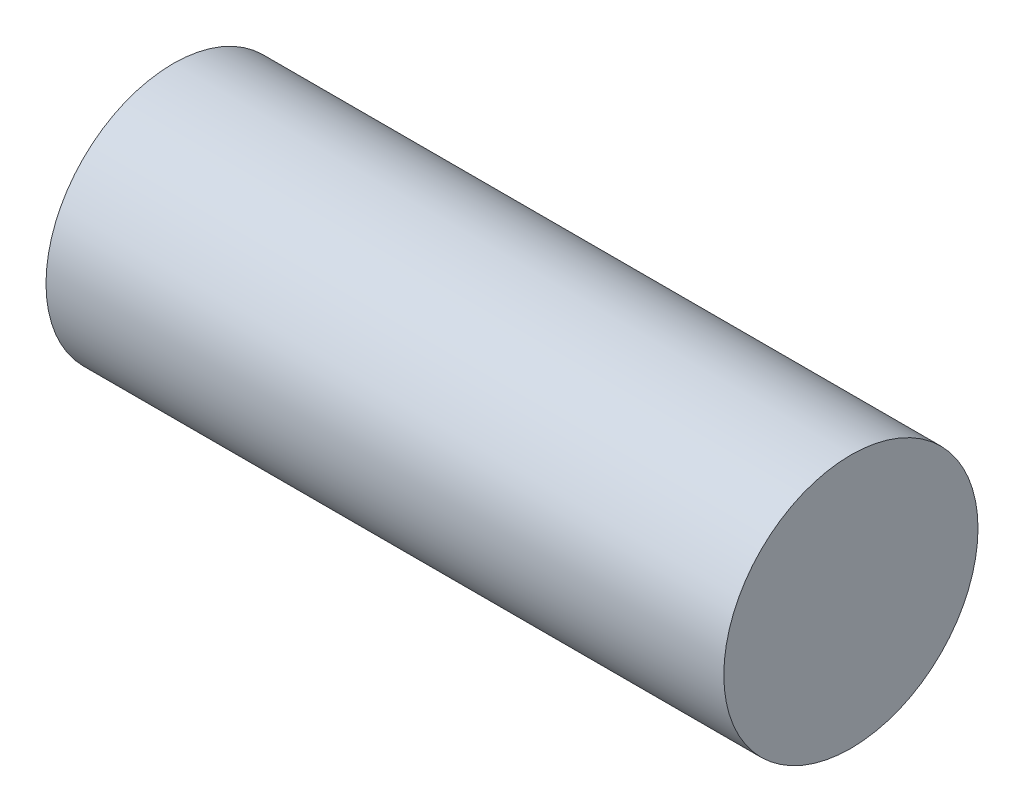
SolidWorks part; units mm, degrees
material "AISI 316 Annealed Stainless Steel Bar (SS)"
ref_plane "Front Plane" through (0, 0, 0) normal (0, 0, 1) x (1, 0, 0)
ref_plane "Top Plane" through (0, 0, 0) normal (0, 1, 0) x (1, 0, 0)
ref_plane "Right Plane" through (0, 0, 0) normal (1, 0, 0) x (0, 0, -1)
sketch "Sketch2" plane through (0, 0, 0) normal (1, 0, 0) x (0, 0, -1)
  circle A0 centre (0, 0) radius 3
  dimension "D1" = 6
extrude "Boss-Extrude2" add sketch "Sketch2" along normal blind 16
